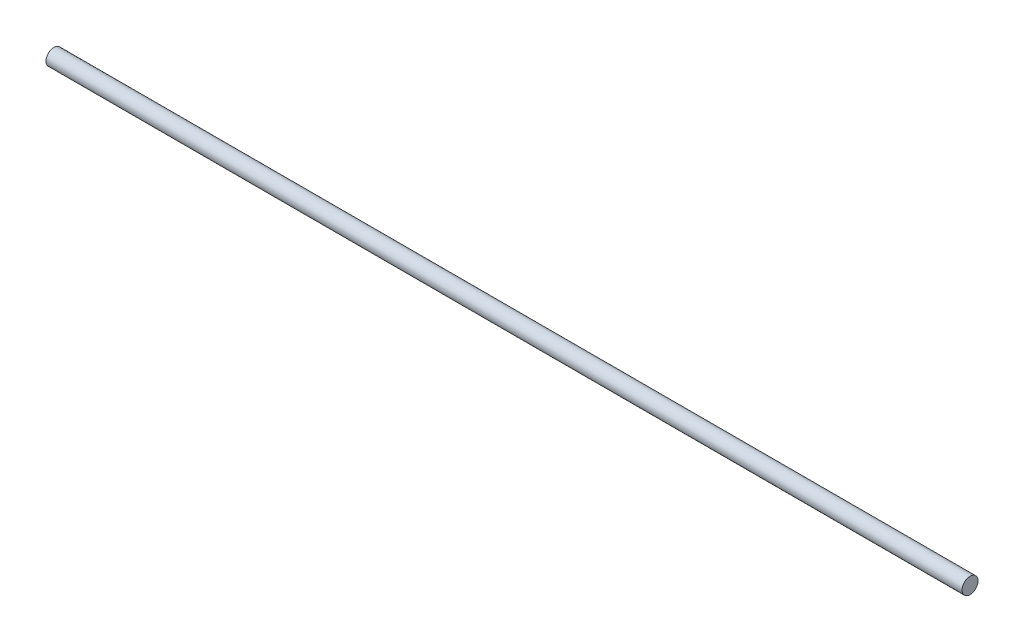
SolidWorks part; units mm, degrees
ref_plane "Front Plane" through (0, 0, 0) normal (0, 0, 1) x (1, 0, 0)
ref_plane "Top Plane" through (0, 0, 0) normal (0, 1, 0) x (1, 0, 0)
ref_plane "Right Plane" through (0, 0, 0) normal (1, 0, 0) x (0, 0, -1)
sketch "Sketch4" plane through (0, 0, 0) normal (1, 0, 0) x (0, 0, -1)
  circle A0 centre (0, 0) radius 4
  dimension "D1" = 8
extrude "Boss-Extrude1" add sketch "Sketch4" along normal blind 460
